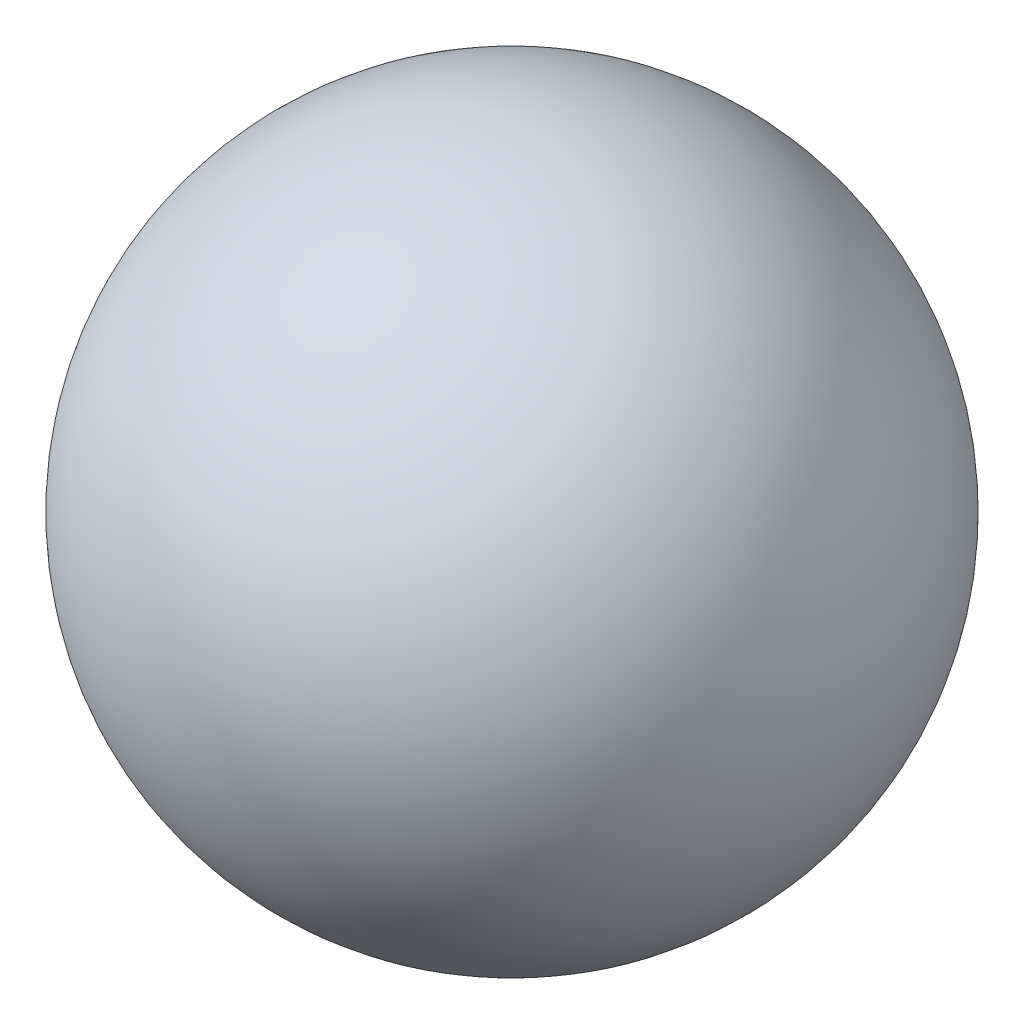
SolidWorks part; units mm, degrees
ref_plane "Front Plane" through (0, 0, 0) normal (0, 0, 1) x (1, 0, 0)
ref_plane "Top Plane" through (0, 0, 0) normal (0, 1, 0) x (1, 0, 0)
ref_plane "Right Plane" through (0, 0, 0) normal (1, 0, 0) x (0, 0, -1)
sketch "Sketch1" plane through (0, 0, 0) normal (0, 0, 1) x (1, 0, 0)
  line L0 (0, 0) -> (0, 45.5406) construction
  circle A0 centre (0, 0) radius 21.5
  dimension "D1" = 43
revolve "Revolve2" add sketch "Sketch1" angle 360 about L0
sketch "Sketch2" plane through (0, 0, 0) normal (1, 0, 0) x (0, 0, -1)
  line L0 (0, 0) -> (0, 12.0099) construction
